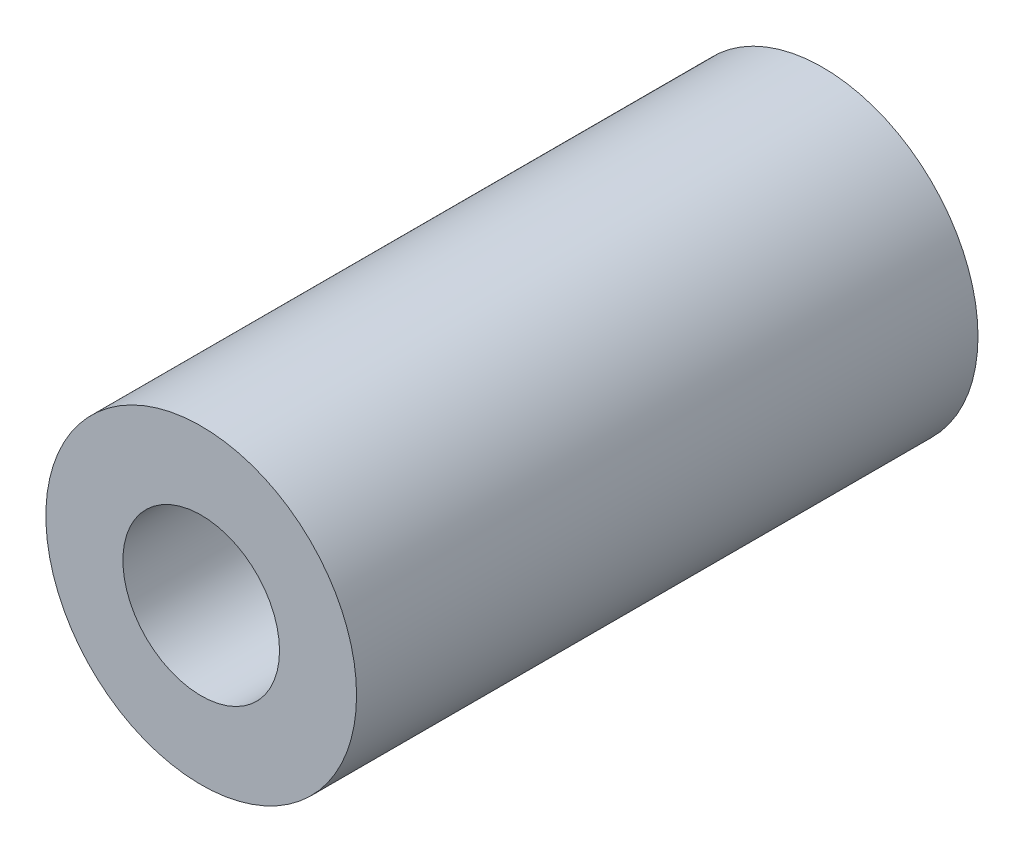
SolidWorks part; units mm, degrees
ref_plane "Front Plane" through (0, 0, 0) normal (0, 0, 1) x (1, 0, 0)
ref_plane "Top Plane" through (0, 0, 0) normal (0, 1, 0) x (1, 0, 0)
ref_plane "Right Plane" through (0, 0, 0) normal (1, 0, 0) x (0, 0, -1)
sketch "Sketch1" plane through (0, 0, 0) normal (0, 0, 1) x (1, 0, 0)
  circle A0 centre (0, 0) radius 6.35
  circle A1 centre (0, 0) radius 3.2004
  dimension "OD" = 12.7
  dimension "ID" = 6.4008
extrude "Extrude1" add sketch "Sketch1" along normal mid plane 25.4
sketch "Sketch2" plane through (0, 0, 0) normal (1, 0, 0) x (0, 0, -1)
  line L0 (-12.7, -3.2004) -> (12.7, -3.2004) construction
  line L3 (12.7, 3.2004) -> (-12.7, 3.2004) construction
  line L5 (-12.7, -3.2004) -> (12.7, -3.2004)
  line L6 (12.7, 3.2004) -> (-12.7, 3.2004)
sketch "Sketch4" plane through (0, 0, 12.7) normal (0, 0, 1) x (1, 0, 0)
  line L0 (0, 0) -> (-2.263, 2.263)
  line L1 (0, -6.985) -> (0, 6.985) construction
  circle A0 centre (0, 0) radius 3.2004 construction
  dimension "D1" = 45
